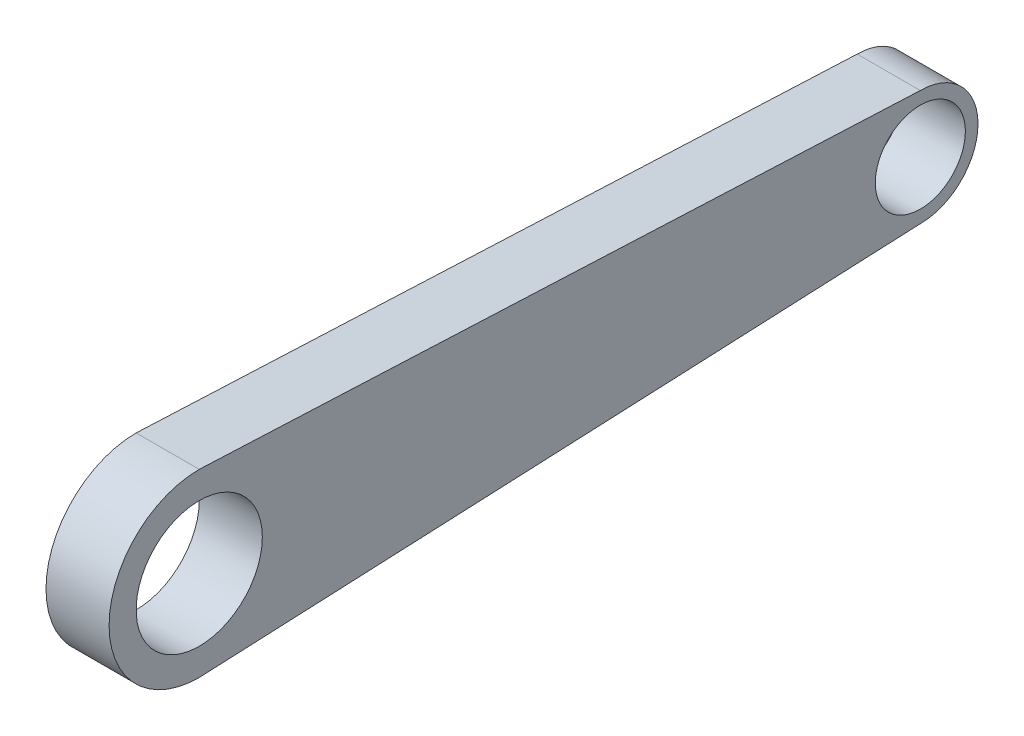
SolidWorks part; units mm, degrees
material "1.4000 (X6Cr13)"
ref_plane "前视基准面" through (0, 0, 0) normal (0, 0, 1) x (1, 0, 0)
ref_plane "上视基准面" through (0, 0, 0) normal (0, 1, 0) x (1, 0, 0)
ref_plane "右视基准面" through (0, 0, 0) normal (1, 0, 0) x (0, 0, -1)
sketch "草图3" plane through (0, 0, 0) normal (1, 0, 0) x (0, 0, -1)
  line L1 (0, 5) -> (40, 3.2)
  line L2 (0, -5) -> (40, -3.2)
  circle A0 centre (0, 0) radius 3.5
  arc A1 (0.4491, 4.9798) -> (0.4491, -4.9798) centre (0, 0) ccw
  circle A2 centre (40, 0) radius 2.5
  arc A3 (40, -3.2) -> (40, 3.2) centre (40, 0) ccw
extrude "凸台-拉伸2" add sketch "草图3" along normal blind 3.5 contours L2 A3 L1 A1 A0 A2
